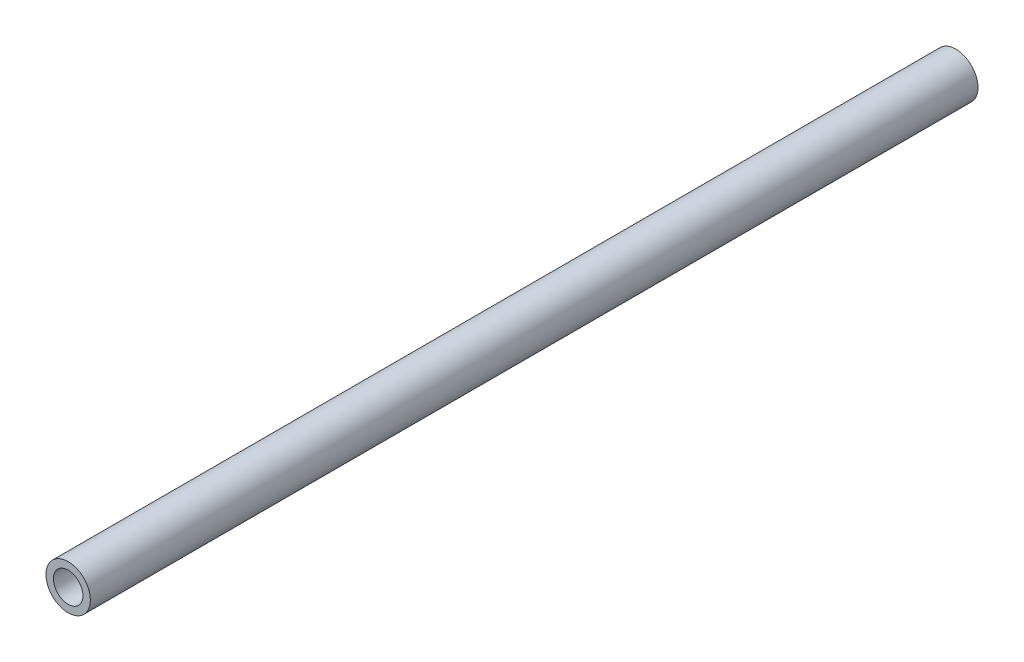
SolidWorks part; units mm, degrees
material "AFL carbon fiber"
ref_plane "Front Plane" through (0, 0, 0) normal (0, 0, 1) x (1, 0, 0)
ref_plane "Top Plane" through (0, 0, 0) normal (0, 1, 0) x (1, 0, 0)
ref_plane "Right Plane" through (0, 0, 0) normal (1, 0, 0) x (0, 0, -1)
sketch "Sketch1" plane through (0, 0, 0) normal (0, 0, 1) x (1, 0, 0)
  circle A0 centre (0, 0) radius 6.35
  circle A1 centre (0, 0) radius 9.525
  dimension "D1" = 12.7
  dimension "D2" = 19.05
extrude "Boss-Extrude1" add sketch "Sketch1" along normal blind 381
equation "\"D1@Boss-Extrude1\"= \"boom_len\"/2"
equation "\"span\"= 48"
equation "\"wing_chord\"= 9"
equation "\"fuse_len\"= 15"
equation "\"fuse_height\"= 5"
equation "\"fuse_wid\"= 5"
equation "\"foam_t\"= 0.1875"
equation "\"main_spar_len\"= 36"
equation "\"x_fuse_to_wing\"= 3"
equation "\"x_cg_from_le\"= 2.25"
equation "\"boom_len\"= 30"
equation "\"wing_angle\"= 1.5"
equation "\"boom_d\"= 0.75"
equation "\"wing_spar_d\"= 0.375"
equation "\"wing_spar_l\"= 48"
equation "\"wing_spar_spacing\"= 1.35"
equation "\"wing_mount_l\"= 2.5"
equation "\"boom_mount_l\"= 1"
equation "\"vstab_span\"= 6.5"
equation "\"hstab_span\"= 15.25"
equation "\"tail_chord\"= 5"
